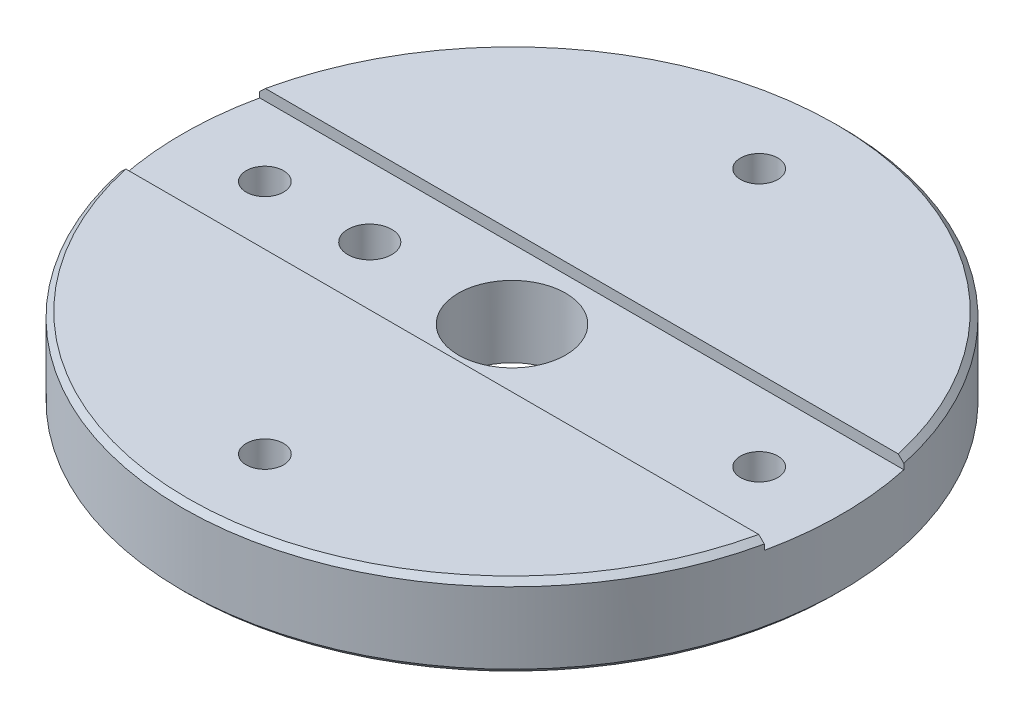
SolidWorks part; units mm, degrees
material "Plain Carbon Steel"
ref_plane "Front Plane" through (0, 0, 0) normal (0, 0, 1) x (1, 0, 0)
ref_plane "Top Plane" through (0, 0, 0) normal (0, 1, 0) x (1, 0, 0)
ref_plane "Right Plane" through (0, 0, 0) normal (1, 0, 0) x (0, 0, -1)
sketch "Sketch1" plane through (0, 0, 0) normal (0, 1, 0) x (1, 0, 0)
  circle A0 centre (0, 0) radius 60
  circle A1 centre (0, 0) radius 9.765
  dimension "D1" = 120
  dimension "D2" = 19.53
extrude "Boss-Extrude1" add sketch "Sketch1" against normal blind 15
chamfer "Chamfer1" distance 1 angle 45 2 edges at (0, -15, 60) (0, 0, 60)
hole_wizard "M8 Tapped Hole1" positions "Sketch6" profile "Sketch3" tap size "M8" standard "ISO" end condition through all
sketch "Sketch6" plane through (0, 0, 0) normal (0, 1, 0) x (1, 0, 0)
  line L0 (0, -45) -> (0, 45) construction
  line L2 (-45, 0) -> (45, 0) construction
  circle A0 centre (0, 0) radius 45
  point P10 (0, -45)
  point P11 (0, 45)
  point P14 (-45, 0)
  point P15 (45, 0)
  point P59 (0, 45)
  point P61 (45, 0)
  point P63 (0, -45)
  point P65 (-45, 0)
  dimension "D1" = 90
sketch "Sketch3" plane through (-45, 0, 0) normal (1, 0, 0) x (0, 0, 1)
  line L0 (0, 0) -> (0, 15)
  line L1 (0, 15) -> (3.4, 15)
  line L2 (3.4, 15) -> (3.4, 0)
  line L5 (3.4, 0) -> (0, 0)
  line L11 (0, -6.35) -> (0, 107.95) construction
  dimension "Thru Tap Drill Dia." = 6.8
  dimension "Thru Tap Drill Depth" = 15
cosmetic thread "Hole Thread1" parameters "D2"=8
cosmetic thread "Hole Thread2" parameters "D2"=8
cosmetic thread "Hole Thread3" parameters "D2"=8
cosmetic thread "Hole Thread4" parameters "D2"=8
sketch "Sketch5" plane through (0, -15, 0) normal (0, -1, 0) x (1, 0, 0)
  line L0 (0, 0) -> (0, 45) construction
  circle A0 centre (0, 0) radius 45 construction
  circle A1 centre (0, 45) radius 10
  dimension "D1" = 0
  dimension "D2" = 20
extrude "Cut-Extrude1" cut sketch "Sketch5" against normal blind 3 contours A1
pattern_circular "CirPattern1" count 12 every 30 about axis through (0, 0, 0) along (0, 1, 0) of "Cut-Extrude1"
sketch "Sketch7" plane through (0, 0, 0) normal (0, 1, 0) x (1, 0, 0)
  line L1 (-60, -12.7) -> (60, -12.7)
  line L2 (-60, -12.7) -> (-60, 12.7)
  line L3 (-60, 12.7) -> (60, 12.7)
  line L4 (60, -12.7) -> (60, 12.7)
  line L5 (-60, -12.7) -> (60, 12.7) construction
  line L6 (-60, 12.7) -> (60, -12.7) construction
  circle A0 centre (0, 0) radius 60 construction
  point P0 (0, 0)
  dimension "D1" = 25.4
extrude "Cut-Extrude2" cut sketch "Sketch7" against normal blind 2 contours L3 L4 L1 L2
sketch "Sketch8" plane through (0, 0, 0) normal (0, 1, 0) x (1, 0, 0)
  circle A0 centre (-25.9, 0) radius 4
  dimension "D1" = 25.9
  dimension "D2" = 8
extrude "Cut-Extrude3" cut sketch "Sketch8" against normal up to next and the other way through all
